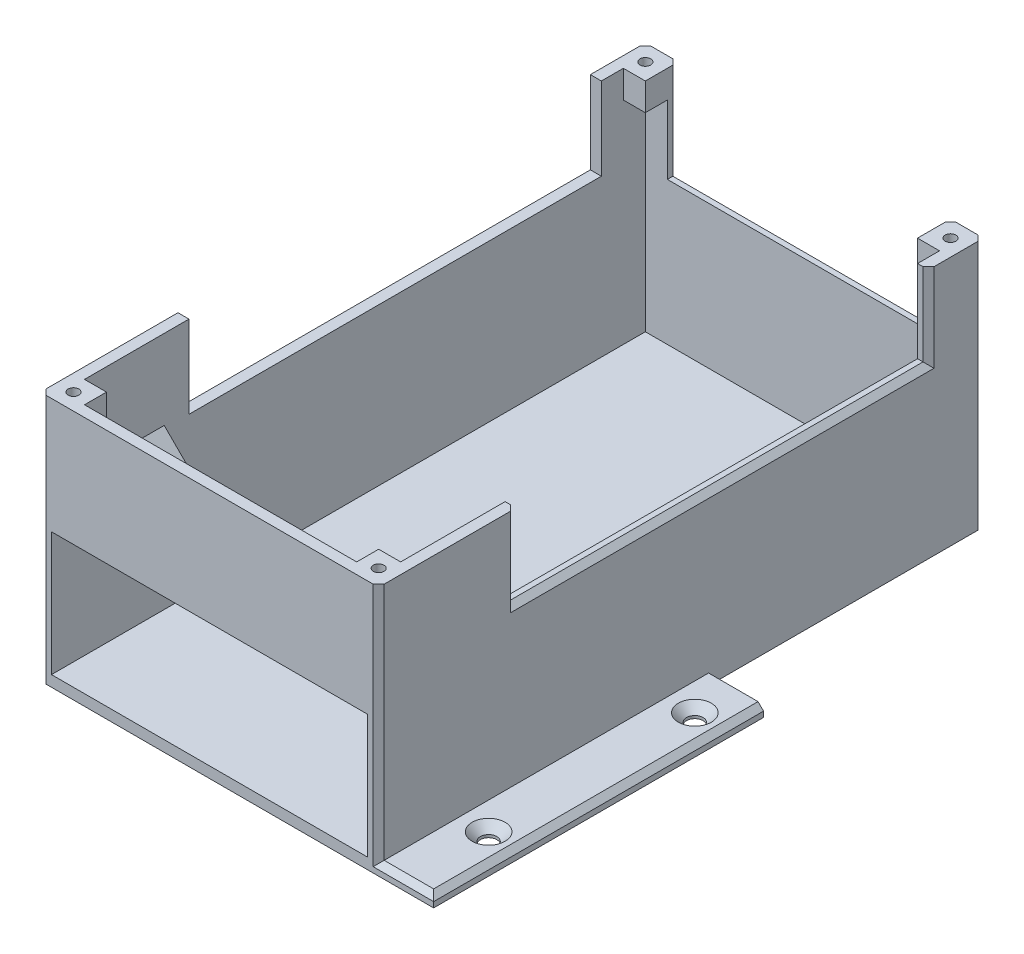
SolidWorks part; units mm, degrees
ref_plane "Front Plane" through (0, 0, 0) normal (0, 0, 1) x (1, 0, 0)
ref_plane "Top Plane" through (0, 0, 0) normal (0, 1, 0) x (1, 0, 0)
ref_plane "Right Plane" through (0, 0, 0) normal (1, 0, 0) x (0, 0, -1)
sketch "Sketch1" plane through (0, 0, 0) normal (0, 1, 0) x (1, 0, 0)
  line L1 (0, 0) -> (123, 0)
  line L2 (0, 0) -> (0, 220)
  line L3 (0, 220) -> (123, 220)
  line L4 (123, 0) -> (123, 220)
  dimension "D1" = 123
  dimension "D2" = 220
extrude "Boss-Extrude1" add sketch "Sketch1" along normal blind 4
sketch "Sketch2" plane through (0, 4, 0) normal (0, 1, 0) x (1, 0, 0)
  line L0 (0, 0) -> (123, 0) construction
  line L1 (123, 0) -> (123, 220) construction
  line L2 (123, 220) -> (0, 220) construction
  line L3 (0, 220) -> (0, 0) construction
  line L4 (0, 0) -> (123, 0)
  line L5 (123, 0) -> (123, 220)
  line L6 (123, 220) -> (0, 220)
  line L7 (0, 220) -> (0, 0)
  line L8 (4, 216) -> (4, 4)
  line L9 (4, 4) -> (119, 4)
  line L10 (119, 4) -> (119, 216)
  line L11 (119, 216) -> (4, 216)
  dimension "D1" = 4
extrude "Boss-Extrude2" add sketch "Sketch2" along normal blind 87
sketch "Sketch3" plane through (0, 0, 0) normal (0, 0, 1) x (1, 0, 0)
  line L4 (4, 4) -> (119, 4)
  line L5 (4, 91) -> (4, 4)
  line L6 (119, 91) -> (4, 91)
  line L7 (119, 4) -> (119, 91)
  line L8 (4, 4) -> (119, 4)
  line L9 (4, 49) -> (4, 4)
  line L10 (119, 49) -> (4, 49)
  line L11 (119, 4) -> (119, 49)
  dimension "D2" = 45
  dimension "D1" = 0
extrude "Cut-Extrude1" cut sketch "Sketch3" against normal up to next
sketch "Sketch4" plane through (123, 0, 0) normal (1, 0, 0) x (0, 0, -1)
  line L0 (0, 91) -> (220, 91) construction
  line L1 (50, 91) -> (200, 91)
  line L2 (50, 91) -> (50, 61)
  line L3 (50, 61) -> (200, 61)
  line L4 (200, 91) -> (200, 61)
  line L5 (220, 91) -> (220, 0) construction
  line L6 (0, 91) -> (0, 0) construction
  dimension "D1" = 30
  dimension "D2" = 20
  dimension "D3" = 50
extrude "Cut-Extrude2" cut sketch "Sketch4" against normal through all
ref_plane "Plane1" through (0, 49, 0) normal (0, -1, 0) x (-1, 0, 0)
sketch "Sketch6" plane through (0, 49, 0) normal (0, -1, 0) x (-1, 0, 0)
  line L0 (-119, 0) -> (-119, 216) construction
  line L1 (-4, 4) -> (-119, 4) construction
  line L2 (-4, 4) -> (-4, 41)
  line L3 (-4, 41) -> (-119, 41) construction
  line L4 (-119, 4) -> (-119, 41)
  line L5 (-61.5, 41) -> (-61.5, 4) construction
  line L6 (-95, 41) -> (-95, 4)
  line L7 (-28, 41) -> (-28, 4)
  line L8 (-4, 41) -> (-28, 41)
  line L9 (-4, 4) -> (-28, 4)
  line L10 (-95, 4) -> (-119, 4)
  line L11 (-95, 41) -> (-119, 41)
  line L12 (-4, 22.5) -> (-119, 22.5) construction
  circle A0 centre (-25, 27.5) radius 1.45
  circle A1 centre (-25, 17.5) radius 1.45
  circle A2 centre (-98, 17.5) radius 1.45
  circle A3 centre (-98, 27.5) radius 1.45
  dimension "D4" = 2.9
  dimension "D1" = 37
  dimension "D5" = 3
  dimension "D6" = 5
  dimension "D2" = 33.5
  dimension "D3" = 33.5
extrude "Boss-Extrude4" add sketch "Sketch6" against normal blind 3
sketch "Sketch8" plane through (0, 91, 0) normal (0, 1, 0) x (1, 0, 0)
  line L0 (0, 110) -> (123, 110) construction
  line L3 (61.5, 220) -> (61.5, 0) construction
  line L4 (123, 220) -> (0, 220) construction
  line L5 (0, 0) -> (123, 0) construction
  line L6 (123, 208) -> (111, 208)
  line L7 (0, 220) -> (12, 220)
  line L8 (0, 220) -> (0, 208)
  line L9 (0, 208) -> (12, 208)
  line L10 (12, 220) -> (12, 208)
  line L11 (111, 220) -> (111, 208)
  line L12 (123, 220) -> (111, 220)
  line L13 (123, 220) -> (123, 208)
  line L24 (123, 0) -> (123, 12)
  line L25 (123, 0) -> (111, 0)
  line L26 (111, 0) -> (111, 12)
  line L27 (123, 12) -> (111, 12)
  line L28 (0, 12) -> (12, 12)
  line L29 (12, 0) -> (12, 12)
  line L30 (0, 0) -> (12, 0)
  line L31 (0, 0) -> (0, 12)
  dimension "D1" = 12
  dimension "D2" = 12
extrude "Boss-Extrude5" add sketch "Sketch8" against normal blind 10
sketch "Sketch9" plane through (0, 91, 0) normal (0, 1, 0) x (1, 0, 0)
  line L0 (0, 110) -> (123, 110) construction
  line L3 (61.5, 220) -> (61.5, 0) construction
  line L4 (123, 220) -> (0, 220) construction
  line L5 (0, 0) -> (123, 0) construction
  line L6 (12, 208) -> (12, 216) construction
  line L7 (0, 220) -> (12, 220) construction
  line L8 (0, 220) -> (0, 208) construction
  line L9 (0, 208) -> (12, 208) construction
  line L10 (12, 220) -> (12, 208) construction
  line L11 (6, 220) -> (6, 214) construction
  line L12 (6, 214) -> (12, 214) construction
  circle A0 centre (6, 214) radius 1.95
  circle A1 centre (117, 214) radius 1.95
  circle A2 centre (117, 6) radius 1.95
  circle A3 centre (6, 6) radius 1.95
  point P2 (61.5, 110)
  dimension "D1" = 3.9
extrude "Cut-Extrude3" cut sketch "Sketch9" against normal up to next
sketch "Sketch10" plane through (0, 0, -220) normal (0, 0, -1) x (-1, 0, 0)
  line L0 (-123, 91) -> (0, 91) construction
  line L1 (-111, 91) -> (-12, 91)
  line L2 (-111, 91) -> (-111, 56)
  line L3 (-111, 56) -> (-12, 56)
  line L4 (-12, 91) -> (-12, 56)
  point P6 (0, 0)
  dimension "D1" = 35
extrude "Cut-Extrude4" cut sketch "Sketch10" against normal up to next
chamfer "Chamfer1" distance 10 angle 45 2 edges at (119, 52, -22.5) (4, 52, -22.5)
sketch "Sketch11" plane through (0, 0, 0) normal (0, -1, 0) x (1, 0, 0)
  line L5 (123, -50) -> (123, -200) construction
  line L6 (123, -120) -> (143, -120)
  line L7 (123, -120) -> (123, 0)
  line L8 (123, 0) -> (143, 0)
  line L9 (143, -120) -> (143, 0)
  line L10 (123, -220) -> (111, -220) construction
  line L11 (133, -120) -> (133, -30) construction
  circle A2 centre (133, -105) radius 3
  circle A3 centre (133, -30) radius 3
  dimension "D6" = 15
  dimension "D7" = 75
  dimension "D4" = 6
  dimension "D5" = 6
  dimension "D1" = 100
  dimension "D2" = 120
  dimension "D3" = 20
extrude "Boss-Extrude6" add sketch "Sketch11" against normal up to surface (4 mm away) up to face at (61.5, 4, -108)
chamfer "Chamfer3" distance 2 angle 45 12 edges at (133, 4, 0) (0, 45.5, -220) (123, 45.5, -220) (12, 73.5, -220) (61.5, 56, -220) (111, 73.5, -220) (123, 76, -200) (123, 61, -125) (123, 76, -50) (0, 45.5, 0) (123, 47.5, 0) (143, 4, -60)
chamfer "Chamfer4" distance 3 angle 45 2 edges at (133, 4, -33) (133, 4, -108)
